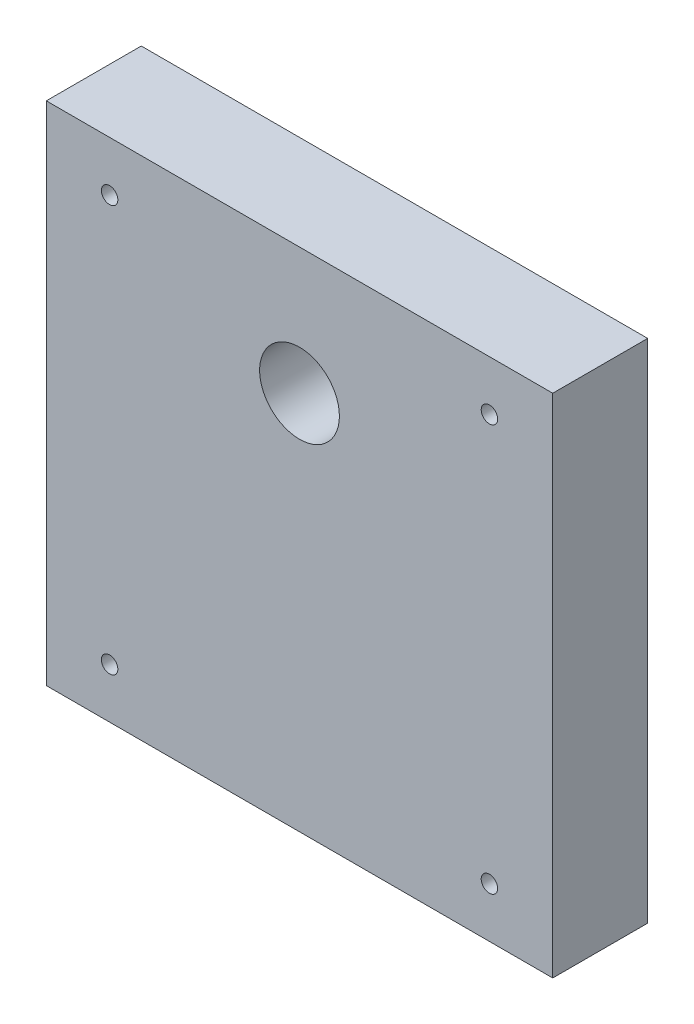
SolidWorks part; units mm, degrees
ref_plane "Front Plane" through (0, 0, 0) normal (0, 0, 1) x (1, 0, 0)
ref_plane "Top Plane" through (0, 0, 0) normal (0, 1, 0) x (1, 0, 0)
ref_plane "Right Plane" through (0, 0, 0) normal (1, 0, 0) x (0, 0, -1)
sketch "Sketch1" plane through (0, 0, 0) normal (0, 0, 1) x (1, 0, 0)
  line L1 (-50.8, 50.8) -> (50.8, 50.8)
  line L2 (-50.8, 50.8) -> (-50.8, -50.8)
  line L3 (-50.8, -50.8) -> (50.8, -50.8)
  line L4 (50.8, 50.8) -> (50.8, -50.8)
  line L5 (-50.8, 50.8) -> (50.8, -50.8) construction
  line L6 (-50.8, -50.8) -> (50.8, 50.8) construction
  point P0 (0, 0)
  dimension "D1" = 101.6
  dimension "D2" = 101.6
extrude "Boss-Extrude1" add sketch "Sketch1" along normal blind 19.05 contours L1 L4 L3 L2
sketch "Sketch2" plane through (0, 0, 19.05) normal (0, 0, 1) x (1, 0, 0)
  circle A0 centre (0, 25.4) radius 8.001
  dimension "D3" = 16.002
extrude "Cut-Extrude1" cut sketch "Sketch2" against normal blind 19.05
sketch "Sketch3" plane through (0, 0, 19.05) normal (0, 0, 1) x (1, 0, 0)
  line L0 (-50.8, 50.8) -> (-50.8, -50.8) construction
  line L1 (-50.8, -50.8) -> (50.8, -50.8) construction
  line L2 (-39.751, -40.767) -> (-38.1, -40.767)
  circle A0 centre (-38.1, -40.767) radius 1.651
  dimension "D1" = 3.302
  dimension "D2" = 12.7
  dimension "D3" = 10.033
extrude "Cut-Extrude2" cut sketch "Sketch3" against normal blind 19.05
sketch "Sketch4" plane through (0, 0, 19.05) normal (0, 0, 1) x (1, 0, 0)
  line L0 (-50.8, 50.8) -> (50.8, 50.8) construction
  line L1 (-50.8, 50.8) -> (-50.8, -50.8) construction
  line L2 (50.8, 50.8) -> (50.8, -50.8) construction
  line L3 (-50.8, -50.8) -> (50.8, -50.8) construction
  circle A0 centre (-38.1, 40.767) radius 1.651
  circle A1 centre (38.1, 40.767) radius 1.651
  circle A2 centre (38.1, -40.767) radius 1.651
  point P4 (-82.9071, 56.4968)
  dimension "D7" = 3.302
  dimension "D8" = 3.302
  dimension "D9" = 3.302
  dimension "D1" = 10.033
  dimension "D2" = 12.7
  dimension "D3" = 12.7
  dimension "D4" = 10.033
  dimension "D5" = 12.7
  dimension "D6" = 10.033
extrude "Cut-Extrude3" cut sketch "Sketch4" against normal blind 19.05 contours A0 | A2 | A1
ref_plane "Plane1" through (-50.8, -50.8, 19.05) normal (0, -1, 0) x (-1, 0, 0)
sketch "Sketch5" plane through (-50.8, -50.8, 19.05) normal (0, -1, 0) x (1, 0, 0)
  line L0 (0, -19.05) -> (101.6, -19.05) construction
  circle A0 centre (12.7, -9.525) radius 2.413
  circle A1 centre (88.9, -9.525) radius 2.413
  dimension "D2" = 4.826
  dimension "D3" = 4.826
  dimension "D1" = 9.525
  dimension "D4" = 9.525
